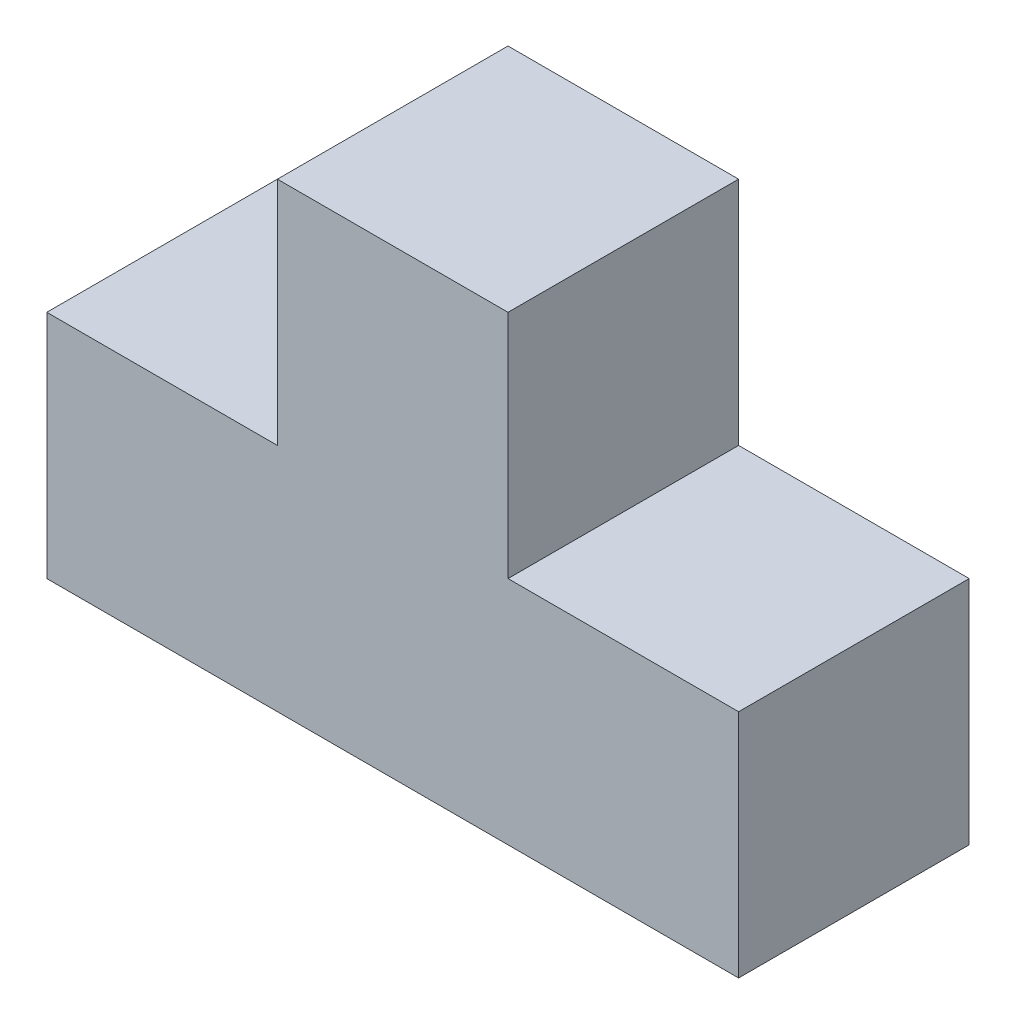
SolidWorks part; units mm, degrees
ref_plane "Plan de face" through (0, 0, 0) normal (0, 0, 1) x (1, 0, 0)
ref_plane "Plan de dessus" through (0, 0, 0) normal (0, 1, 0) x (1, 0, 0)
ref_plane "Plan de droite" through (0, 0, 0) normal (1, 0, 0) x (0, 0, -1)
sketch "Esquisse1" plane through (0, 0, 0) normal (0, 0, 1) x (1, 0, 0)
  line L0 (0, 0) -> (30, 0)
  line L1 (30, 0) -> (30, 10)
  line L2 (20, 10) -> (20, 20)
  line L3 (20, 20) -> (10, 20)
  line L4 (10, 20) -> (10, 10)
  line L5 (10, 10) -> (0, 10)
  line L6 (0, 10) -> (0, 0)
  line L7 (30, 10) -> (20, 10)
  dimension "D1" = 30
  dimension "D2" = 10
  dimension "D3" = 10
  dimension "D4" = 10
  dimension "D5" = 10
  dimension "D6" = 20
extrude "Boss.-Extru.1" add sketch "Esquisse1" against normal blind 10 contours L0 L1 L7 L2 L3 L4 L5 L6
